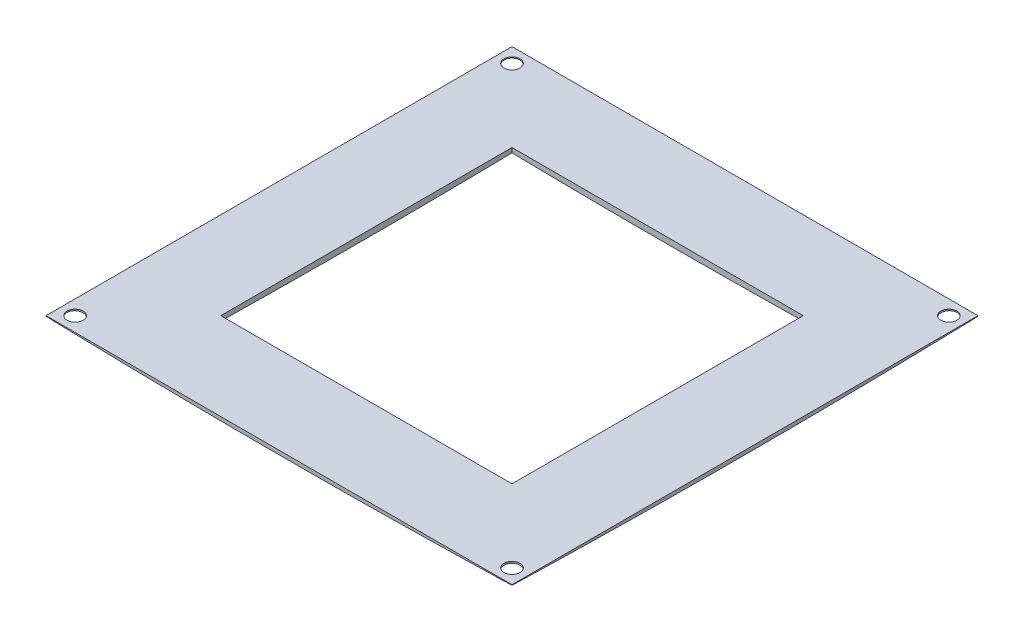
SolidWorks part; units mm, degrees
material "Nylon 101"
ref_plane "Front Plane" through (0, 0, 0) normal (0, 0, 1) x (1, 0, 0)
ref_plane "Top Plane" through (0, 0, 0) normal (0, 1, 0) x (1, 0, 0)
ref_plane "Right Plane" through (0, 0, 0) normal (1, 0, 0) x (0, 0, -1)
sketch "Sketch1" plane through (0, 0, 0) normal (0, 1, 0) x (1, 0, 0)
  line L1 (-101.6, 101.6) -> (101.6, 101.6)
  line L2 (-101.6, 101.6) -> (-101.6, -101.6)
  line L3 (-101.6, -101.6) -> (101.6, -101.6)
  line L4 (101.6, 101.6) -> (101.6, -101.6)
  line L5 (-101.6, 101.6) -> (101.6, -101.6) construction
  line L6 (-101.6, -101.6) -> (101.6, 101.6) construction
  point P0 (0, 0)
  dimension "D1" = 203.2
  dimension "D2" = 203.2
sketch "Sketch3" plane through (0, 0, 0) normal (1, 0, 0) x (0, 0, -1)
  line L0 (0, 0) -> (0, 1044.8052)
  ellipse E0 centre (0, 522.4026) end of major axis (1360.7643, 522.4026) minor radius 522.4026 (0, 1044.8052) -> (0, 0) ccw
revolve "Revolve1" add sketch "Sketch3" angle 360 about L0
extrude "Cut-Extrude1" cut sketch "Sketch1" along normal through all flip side to cut
sketch "Sketch5" plane through (0, 0, 0) normal (0, 1, 0) x (1, 0, 0)
  line L1 (117.262, 126.6503) -> (-117.262, 126.6503)
  line L2 (117.262, 126.6503) -> (117.262, -126.6503)
  line L3 (117.262, -126.6503) -> (-117.262, -126.6503)
  line L4 (-117.262, 126.6503) -> (-117.262, -126.6503)
  line L5 (117.262, 126.6503) -> (-117.262, -126.6503) construction
  line L6 (117.262, -126.6503) -> (-117.262, 126.6503) construction
  point P0 (0, 0)
extrude "Cut-Extrude2" cut sketch "Sketch5" along normal through all from offset 3.175
sketch "Sketch6" plane through (0, 3.175, 0) normal (0, 1, 0) x (1, 0, 0)
  line L0 (-101.6, -101.6) -> (-101.6, 101.6) construction
  line L1 (-63.5, 63.5) -> (63.5, 63.5)
  line L2 (-63.5, 63.5) -> (-63.5, -63.5)
  line L3 (-63.5, -63.5) -> (63.5, -63.5)
  line L4 (63.5, 63.5) -> (63.5, -63.5)
  line L5 (-63.5, 63.5) -> (63.5, -63.5) construction
  line L6 (-63.5, -63.5) -> (63.5, 63.5) construction
  line L7 (101.6, -101.6) -> (-101.6, -101.6) construction
  line L8 (-101.6, 101.6) -> (101.6, 101.6) construction
  line L9 (101.6, 101.6) -> (101.6, -101.6) construction
  circle A0 centre (-95.25, -95.25) radius 3.4925
  circle A1 centre (-95.25, 95.25) radius 3.4925
  circle A2 centre (95.25, 95.25) radius 3.4925
  circle A3 centre (95.25, -95.25) radius 3.4925
  point P0 (0, 0)
  dimension "D3" = 6.985
  dimension "D1" = 127
  dimension "D2" = 127
  dimension "D4" = 6.35
  dimension "D5" = 6.35
  dimension "D6" = 6.35
  dimension "D7" = 6.35
extrude "Cut-Extrude3" cut sketch "Sketch6" against normal through all
